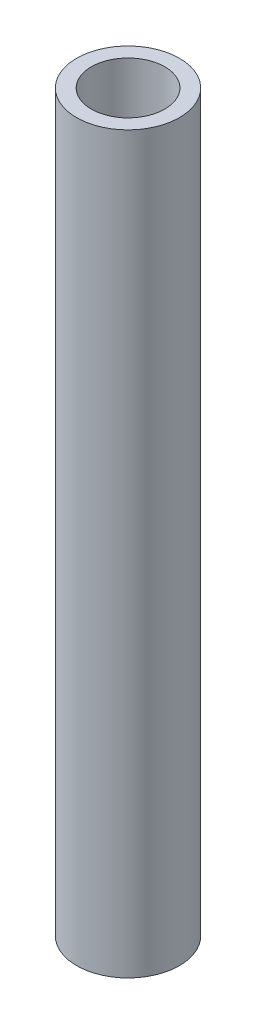
SolidWorks part; units mm, degrees
material "Custom Plastic"
ref_plane "Front Plane" through (0, 0, 0) normal (0, 0, 1) x (1, 0, 0)
ref_plane "Top Plane" through (0, 0, 0) normal (0, 1, 0) x (1, 0, 0)
ref_plane "Right Plane" through (0, 0, 0) normal (1, 0, 0) x (0, 0, -1)
sketch "Sketch1" plane through (0, 0, 0) normal (0, 0, 1) x (1, 0, 0)
  line L0 (0, 0) -> (0, 11.3889) construction
  line L2 (-1.5, 0) -> (-2.1, 0)
  line L3 (-1.5, 0) -> (-1.5, 30)
  line L4 (-1.5, 30) -> (-2.1, 30)
  line L5 (-2.1, 0) -> (-2.1, 30)
  dimension "D1" = 3
  dimension "D2" = 0.6
  dimension "D3" = 30
revolve "Revolve1" add sketch "Sketch1" angle 360 about L0
